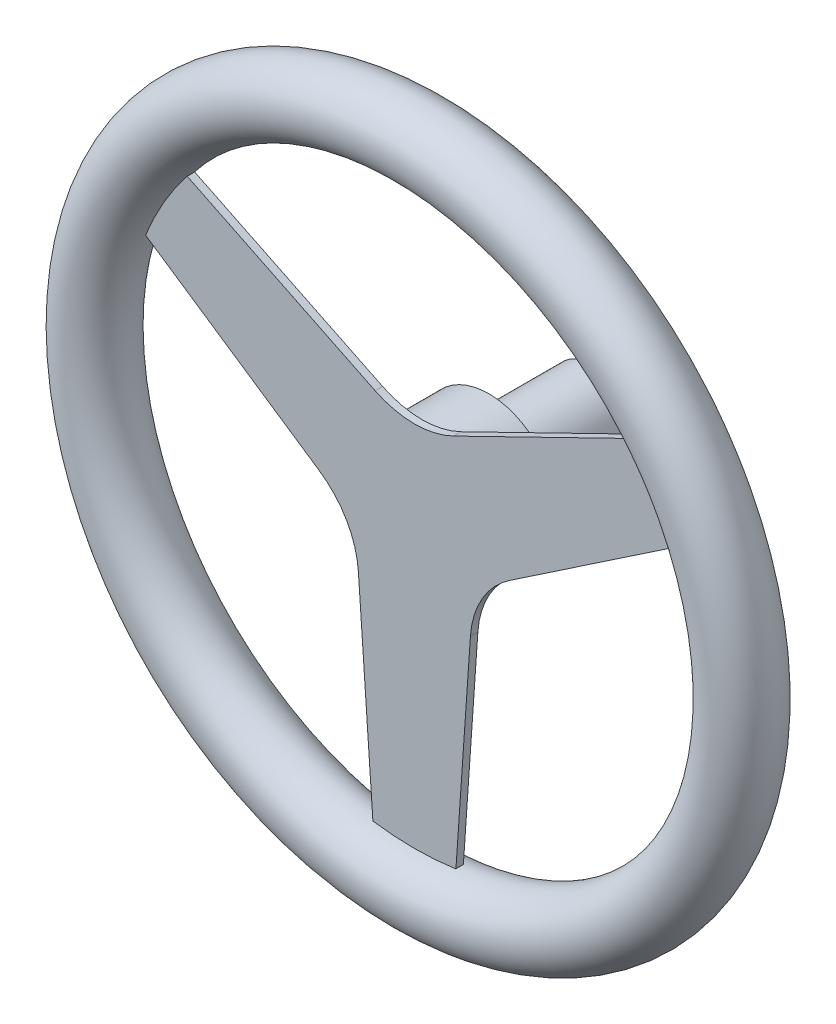
SolidWorks part; units mm, degrees
ref_plane "Front Plane" through (0, 0, 0) normal (0, 0, 1) x (1, 0, 0)
ref_plane "Top Plane" through (0, 0, 0) normal (0, 1, 0) x (1, 0, 0)
ref_plane "Right Plane" through (0, 0, 0) normal (1, 0, 0) x (0, 0, -1)
sketch "Sketch1" plane through (0, 0, 0) normal (1, 0, 0) x (0, 0, -1)
  line L0 (1.4476, 0) -> (-105739.6963, 0) construction
  line L1 (0, 0) -> (0, 137.795) construction
  circle A0 centre (0, 137.795) radius 14.605
  dimension "D1" = 29.21
  dimension "D2" = 304.8
revolve "Revolve1" add sketch "Sketch1" angle 360 about L0
sketch "Sketch2" plane through (0, 0, 0) normal (0, 0, 1) x (1, 0, 0)
  line L0 (-128.3909, 55.0624) -> (-40.573, -4.1246)
  line L1 (-16.51, -138.721) -> (-23.8585, -33.075)
  line L2 (16.51, -138.721) -> (23.8585, -33.075)
  line L3 (40.573, -4.1246) -> (128.3909, 55.0624)
  line L4 (111.8809, 83.6586) -> (16.7145, 37.1996)
  line L5 (-111.8809, 83.6586) -> (-16.7145, 37.1996)
  line L6 (-111.8809, 83.6586) -> (-128.3909, 55.0624)
  line L7 (-16.51, -138.721) -> (16.51, -138.721)
  line L8 (111.8809, 83.6586) -> (128.3909, 55.0624)
  circle A0 centre (0, 0) radius 139.7 construction
  arc A1 (40.573, -4.1246) -> (23.8585, -33.075) centre (61.8667, -35.7187) ccw
  circle A4 centre (0, 0) radius 33.3375 construction
  arc A5 (-40.573, -4.1246) -> (-23.8585, -33.075) centre (-61.8667, -35.7188) cw
  arc A6 (-16.7145, 37.1996) -> (16.7145, 37.1996) centre (0, 71.4375) ccw
  point P0 (0, 0)
  point P2 (0, -138.721)
  dimension "D1" = 66.675
  dimension "D2" = 33.02
  dimension "D3" = 38.1
  dimension "D4" = 279.4
extrude "Boss-Extrude1" add sketch "Sketch2" along normal mid plane 3.175 contours L5 A6 L4 L8 L3 A1 L2 L7 L1 A5 L0 L6
sketch "Sketch3" plane through (0, 0, -1.5875) normal (0, 0, -1) x (-1, 0, 0)
  circle A0 centre (0, 0) radius 28.575
  dimension "D1" = 57.15
extrude "Boss-Extrude2" add sketch "Sketch3" along normal blind 28.575
sketch "Sketch4" plane through (0, 0, -30.1625) normal (0, 0, -1) x (-1, 0, 0)
  circle A0 centre (0, 0) radius 17.4625
  dimension "D1" = 34.925
extrude "Boss-Extrude3" add sketch "Sketch4" along normal blind 43.815
sketch "Sketch6" plane through (0, 0, -73.9775) normal (0, 0, -1) x (-1, 0, 0)
  line L1 (12.7, -7.3323) -> (12.7, 7.3323)
  line L2 (12.7, 7.3323) -> (0, 14.6647)
  line L3 (0, 14.6647) -> (-12.7, 7.3323)
  line L4 (-12.7, 7.3323) -> (-12.7, -7.3323)
  line L5 (-12.7, -7.3323) -> (0, -14.6647)
  line L6 (0, -14.6647) -> (12.7, -7.3323)
  circle A0 centre (0, 0) radius 12.7 construction
  point P1 (0, 0)
  dimension "D1" = 25.4
extrude "Cut-Extrude1" cut sketch "Sketch6" against normal blind 54.61
